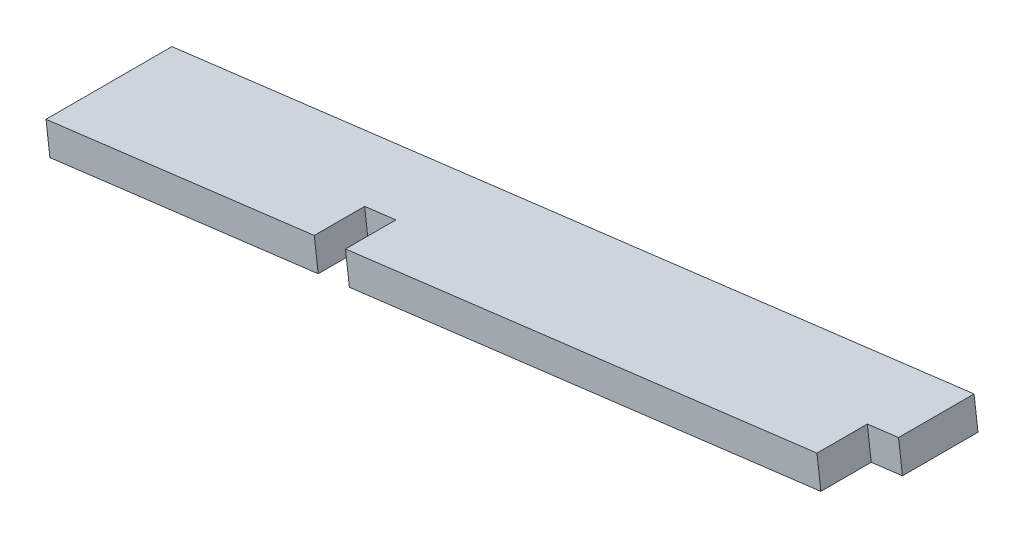
SolidWorks part; units mm, degrees
material "Balsa"
ref_plane "Front Plane" through (0, 0, 0) normal (0, 0, 1) x (1, 0, 0)
ref_plane "Top Plane" through (0, 0, 0) normal (0, 1, 0) x (1, 0, 0)
ref_plane "Right Plane" through (0, 0, 0) normal (1, 0, 0) x (0, 0, -1)
ref_plane "Plane1" through (2.4937, -19.9445, 0) normal (-0.1241, 0.9923, 0) x (0.9923, 0.1241, 0)
sketch "Sketch1" plane through (2.4937, -19.9445, 0) normal (-0.1241, 0.9923, 0) x (0.9923, 0.1241, 0)
  line L0 (374.798, 649.3965) -> (293.2525, 649.3965)
  line L1 (319.2926, 649.3965) -> (318.1896, 649.3965) construction
  line L2 (371.623, 636.6965) -> (323.695, 636.6965)
  line L3 (374.798, 649.3965) -> (374.798, 641.7765)
  line L4 (293.2525, 649.3965) -> (293.2525, 636.6965)
  line L6 (371.623, 636.6965) -> (371.623, 641.7765)
  line L7 (374.7982, 255.6304) -> (374.798, 695.1427)
  line L8 (374.798, 641.7765) -> (374.798, 695.1427) construction
  line L9 (371.623, 641.7765) -> (374.798, 641.7765)
  line L10 (374.798, 636.6965) -> (293.2525, 636.6965) construction
  line L11 (320.5248, 636.6965) -> (320.5248, 641.7765)
  line L12 (320.5248, 641.7765) -> (323.6998, 641.7765)
  line L13 (323.6998, 641.7765) -> (323.695, 636.6965)
  line L14 (320.5248, 636.6965) -> (293.2525, 636.6965)
  line L15 (323.7069, 649.3965) -> (323.6998, 641.7765) construction
  line L18 (293.2525, 636.6965) -> (293.2525, 649.3965) construction
  dimension "D2" = 3.175
  dimension "D3" = 7.62
  dimension "D4" = 3.175
  dimension "D5" = 5.08
  dimension "D1" = 12.7
extrude "Boss-Extrude1" add sketch "Sketch1" along normal blind 3.175 contours L2 L13 L12 L11 L14 L4 L0 L3 L9 L6
